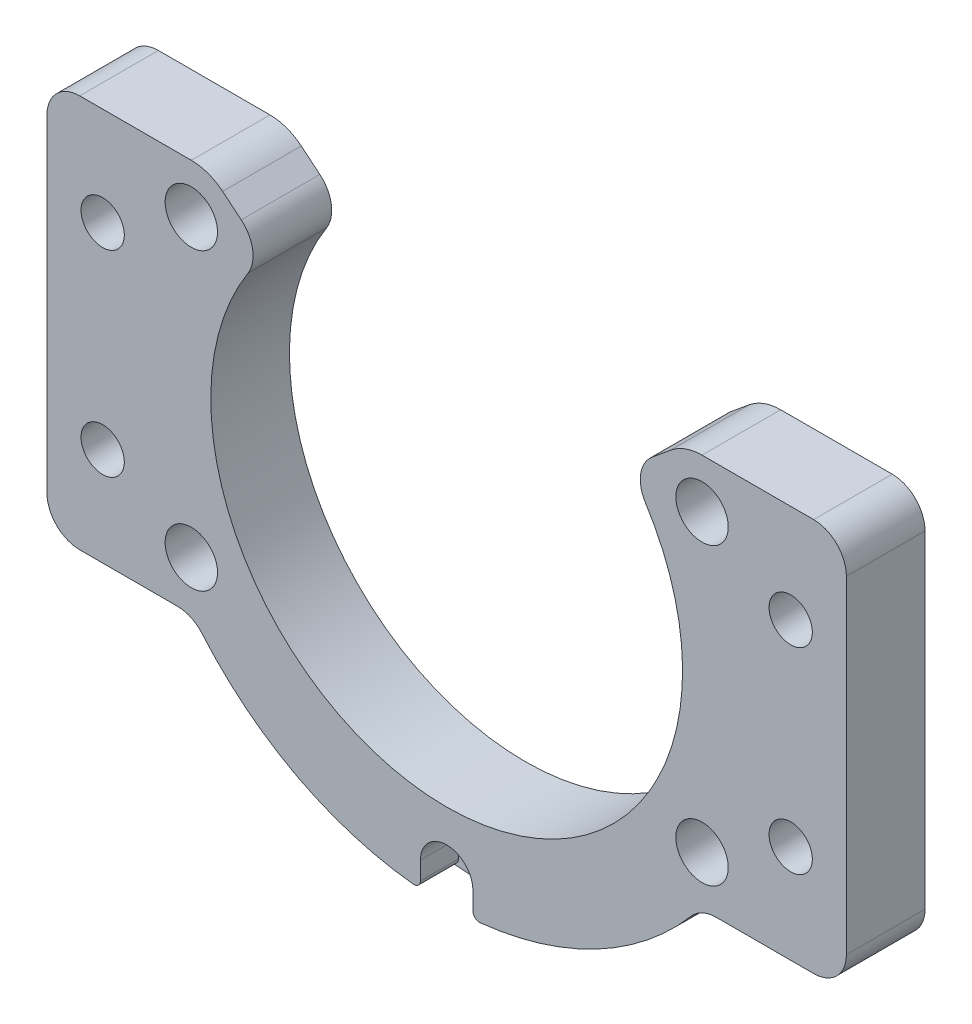
SolidWorks part; units mm, degrees
ref_plane "前视基准面" through (0, 0, 0) normal (0, 0, 1) x (1, 0, 0)
ref_plane "上视基准面" through (0, 0, 0) normal (0, 1, 0) x (1, 0, 0)
ref_plane "右视基准面" through (0, 0, 0) normal (1, 0, 0) x (0, 0, -1)
ref_plane "基准面1" through (0, 0, 0) normal (0, 0, -1) x (-1, 0, 0)
sketch "草图1" plane through (0, 0, 0) normal (0, 0, -1) x (-1, 0, 0)
  line L0 (61, -30) -> (61, 30)
  line L1 (61, 30) -> (-61, 30)
  line L2 (-61, 30) -> (-61, -30)
  line L3 (-61, -30) -> (-38.7427, -30)
  line L4 (38.7427, -30) -> (61, -30)
  arc A0 (-38.7427, -30) -> (38.7427, -30) centre (0, 0) ccw
extrude "凸台-拉伸1" add sketch "草图1" against normal blind 12
sketch "草图2" plane through (0, 0, 12) normal (0, 0, 1) x (1, 0, 0)
  line L0 (-36.2714, 30) -> (0, 0)
  line L1 (0, 0) -> (36.2714, 30)
  line L2 (36.2714, 30) -> (-36.2714, 30)
extrude "切除-拉伸1" cut sketch "草图2" against normal through all
sketch "草图3" plane through (0, 0, 12) normal (0, 0, 1) x (1, 0, 0)
  line L0 (4, -48.8365) -> (4, -45)
  line L1 (-4, -45) -> (-4, -48.8365)
  arc A0 (4, -45) -> (-4, -45) centre (0, -45) ccw
  arc A1 (-4, -48.8365) -> (4, -48.8365) centre (0, 0) ccw
extrude "切除-拉伸2" cut sketch "草图3" against normal blind 5.8
hole_wizard "Ø4.5 (4.5) 直径孔1" positions "草图5" profile "草图4" hole size "Ø4.5" standard "ANSI Metric"
sketch "草图5" plane through (0, 0, 6.2) normal (0, 0, 1) x (1, 0, 0)
  point P0 (0, -45)
sketch "草图4" plane through (0, -45, 6.2) normal (1, 0, 0) x (0, -1, 0)
  line L0 (0, 0) -> (0, 6.2)
  line L1 (0, 6.2) -> (2.25, 6.2)
  line L2 (2.25, 6.2) -> (2.25, 0)
  line L5 (2.25, 0) -> (0, 0)
  line L11 (0, -6.35) -> (0, 107.95) construction
  dimension "通孔孔直径" = 4.5
  dimension "通孔孔深度" = 6.2
hole_wizard "M64 间隙孔1" positions "草图7" profile "草图6" hole size "M64" standard "ANSI Metric"
sketch "草图7" plane through (0, 0, 0) normal (0, 0, -1) x (-1, 0, 0)
  point P0 (0, 0)
sketch "草图6" plane through (0, 0, 0) normal (1, 0, 0) x (0, 1, 0)
  line L0 (0, 0) -> (0, 12)
  line L1 (0, 12) -> (36, 12)
  line L2 (36, 12) -> (36, 0)
  line L5 (36, 0) -> (0, 0)
  line L11 (0, -6.35) -> (0, 107.95) construction
  dimension "通孔孔直径" = 72
  dimension "通孔孔深度" = 12
hole_wizard "M6 六角头螺栓的柱形沉头孔1" positions "草图9" profile "草图8" counterbore size "M6" standard "ANSI Metric"
sketch "草图9" plane through (0, 0, 0) normal (0, 0, -1) x (-1, 0, 0)
  point P0 (-52.5, -15)
  point P1 (52.5, 15)
  point P2 (52.5, -15)
  point P3 (-52.5, 15)
sketch "草图8" plane through (52.5, -15, 0) normal (1, 0, 0) x (0, 1, 0)
  line L0 (0, 0) -> (0, 12)
  line L1 (0, 12) -> (3.3, 12)
  line L3 (3.3, 12) -> (3.3, 6.5)
  line L4 (3.3, 6.5) -> (5.5, 6.5)
  line L5 (5.5, 6.5) -> (5.5, 0)
  line L7 (5.5, 0) -> (0, 0)
  line L11 (0, -6.35) -> (0, 107.95) construction
  dimension "通孔孔直径" = 6.6
  dimension "通孔孔深度" = 12
  dimension "柱形沉头孔直径" = 11
  dimension "柱形沉头孔深度" = 6.5
hole_wizard "M4 六角头机械螺钉的柱形沉头孔1" positions "草图11" profile "草图10" counterbore size "M4" standard "ANSI Metric"
sketch "草图11" plane through (0, 0, 12) normal (0, 0, 1) x (1, 0, 0)
  point P0 (38.9711, 22.5)
  point P1 (38.9711, -22.5)
  point P2 (-38.9711, -22.5)
  point P3 (-38.9711, 22.5)
sketch "草图10" plane through (38.9711, 22.5, 12) normal (1, 0, 0) x (0, -1, 0)
  line L0 (0, 0) -> (0, 12)
  line L1 (0, 12) -> (2.25, 12)
  line L3 (2.25, 12) -> (2.25, 5.8)
  line L4 (2.25, 5.8) -> (4, 5.8)
  line L5 (4, 5.8) -> (4, 0)
  line L7 (4, 0) -> (0, 0)
  line L11 (0, -6.35) -> (0, 107.95) construction
  dimension "通孔孔直径" = 4.5
  dimension "通孔孔深度" = 12
  dimension "柱形沉头孔直径" = 8
  dimension "柱形沉头孔深度" = 5.8
fillet "圆角1" radius 1 2 edges at (-4, -48.8365, 9.1) (4, -48.8365, 9.1)
fillet "圆角2" radius 5 8 edges at (38.7427, -30, 6) (61, -30, 6) (-27.7409, 22.9444, 6) (61, 30, 6) (27.7409, 22.9444, 6) (-61, 30, 6) (-38.7427, -30, 6) (-61, -30, 6)
fillet "圆角3" radius 7.5 2 edges at (36.2714, 30, 6) (-36.2714, 30, 6)
